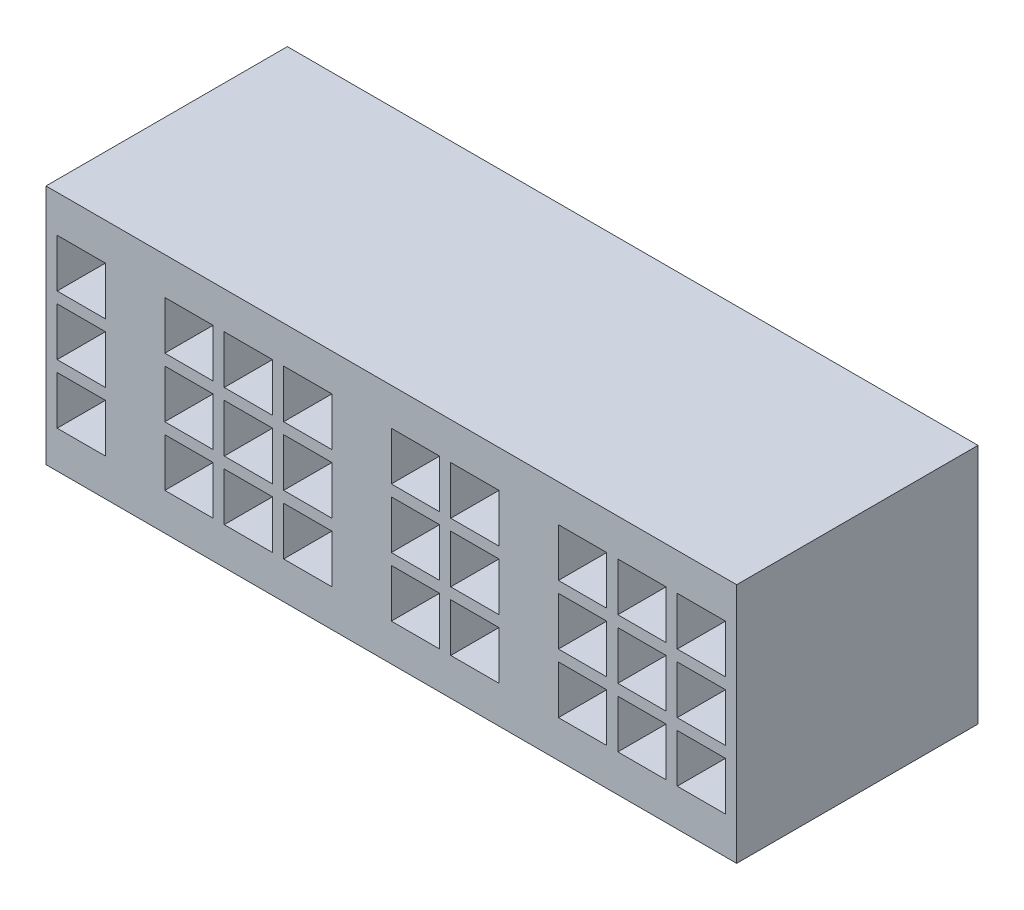
SolidWorks part; units mm, degrees
ref_plane "Plan de face" through (0, 0, 0) normal (0, 0, 1) x (1, 0, 0)
ref_plane "Plan de dessus" through (0, 0, 0) normal (0, 1, 0) x (1, 0, 0)
ref_plane "Plan de droite" through (0, 0, 0) normal (1, 0, 0) x (0, 0, -1)
sketch "Esquisse1" plane through (0, 0, 0) normal (0, 0, 1) x (1, 0, 0)
  line L1 (-93, -51) -> (93, -51)
  line L2 (-93, -51) -> (-93, 0)
  line L3 (-93, 0) -> (93, 0)
  line L4 (93, -51) -> (93, 0)
  line L13 (0, 49979.1071) -> (0, -49979.1071) construction
  point P0 (0, 0)
  point P16 (0, -51)
  point P17 (0, 0)
  point P27 (0, 0)
  dimension "D1" = 186
  dimension "D2" = 51
extrude "Boss.-Extru.1" add sketch "Esquisse1" along normal blind 35
sketch "Esquisse7" plane through (0, 0, 35) normal (0, 0, 1) x (1, 0, 0)
  line L0 (93, 0) -> (-93, 0) construction
  line L1 (-90, -3) -> (-77, -3)
  line L2 (-90, -3) -> (-90, -16)
  line L3 (-90, -16) -> (-77, -16)
  line L4 (-77, -3) -> (-77, -16)
  line L5 (-90, -3) -> (-77, -16) construction
  line L6 (-90, -16) -> (-77, -3) construction
  line L7 (-93, 0) -> (-93, -51) construction
  point P0 (-83.5, -9.5)
  dimension "D1" = 13
  dimension "D2" = 13
  dimension "D3" = 3
  dimension "D4" = 3
extrude "Enlèv. mat.-Extru.5" cut sketch "Esquisse7" against normal blind 91
pattern_linear "Répétition linéaire5" count 3 spacing 16 along (0, -1, 0) of "Enlèv. mat.-Extru.5"
sketch "Esquisse8" plane through (0, 0, 35) normal (0, 0, 1) x (1, 0, 0)
  line L0 (93, 0) -> (-93, 0) construction
  line L1 (-61, -3) -> (-48, -3)
  line L2 (-61, -3) -> (-61, -16)
  line L3 (-61, -16) -> (-48, -16)
  line L4 (-48, -3) -> (-48, -16)
  line L5 (-61, -3) -> (-48, -16) construction
  line L6 (-61, -16) -> (-48, -3) construction
  line L7 (-77, -16) -> (-77, -3) construction
  point P0 (-54.5, -9.5)
  dimension "D1" = 13
  dimension "D2" = 13
  dimension "D3" = 3
  dimension "D4" = 16
extrude "Enlèv. mat.-Extru.6" cut sketch "Esquisse8" against normal blind 103
pattern_linear "Répétition linéaire6" count 3 spacing 16 along (0, -1, 0) count 3 spacing 16 along (1, 0, 0) of "Enlèv. mat.-Extru.6"
sketch "Esquisse9" plane through (0, 0, 35) normal (0, 0, 1) x (1, 0, 0)
  line L0 (-16, -16) -> (-16, -3) construction
  line L1 (0, -3) -> (13, -3)
  line L2 (0, -3) -> (0, -16)
  line L3 (0, -16) -> (13, -16)
  line L4 (13, -3) -> (13, -16)
  line L5 (0, -3) -> (13, -16) construction
  line L6 (0, -16) -> (13, -3) construction
  line L7 (93, 0) -> (-93, 0) construction
  point P0 (6.5, -9.5)
  dimension "D1" = 13
  dimension "D2" = 13
  dimension "D3" = 16
  dimension "D4" = 3
extrude "Enlèv. mat.-Extru.7" cut sketch "Esquisse9" against normal blind 77
pattern_linear "Répétition linéaire7" count 3 spacing 16 along (0, -1, 0) count 2 spacing 16 along (1, 0, 0) of "Enlèv. mat.-Extru.7"
sketch "Esquisse10" plane through (0, 0, 35) normal (0, 0, 1) x (1, 0, 0)
  line L0 (29, -16) -> (29, -3) construction
  line L1 (45, -3) -> (58, -3)
  line L2 (45, -3) -> (45, -16)
  line L3 (45, -16) -> (58, -16)
  line L4 (58, -3) -> (58, -16)
  line L5 (45, -3) -> (58, -16) construction
  line L6 (45, -16) -> (58, -3) construction
  line L7 (93, 0) -> (-93, 0) construction
  point P0 (51.5, -9.5)
  dimension "D1" = 13
  dimension "D2" = 13
  dimension "D3" = 16
  dimension "D4" = 3
extrude "Enlèv. mat.-Extru.8" cut sketch "Esquisse10" against normal blind 78
pattern_linear "Répétition linéaire8" count 3 spacing 16 along (1, 0, 0) count 3 spacing 16 along (0, -1, 0) of "Enlèv. mat.-Extru.8"
sketch "Esquisse14" plane through (0, -51, 0) normal (0, -1, 0) x (1, 0, 0)
  line L0 (0, 0) -> (-15.3262, 0) construction
  line L1 (-12.6631, 0) -> (-2.6631, 0)
  line L2 (-12.6631, 0) -> (-12.6631, 5)
  line L3 (-12.6631, 5) -> (-2.6631, 5)
  line L4 (-2.6631, 0) -> (-2.6631, 5)
  line L5 (-12.6631, 0) -> (-2.6631, 5) construction
  line L6 (-12.6631, 5) -> (-2.6631, 0) construction
  line L7 (-93, 0) -> (93, 0) construction
  point P0 (-7.6631, 2.5)
  point P5 (-15.3262, 0)
  point P6 (0, 0)
  point P10 (0, 0)
  point P12 (-7.6631, 0)
  point P13 (-7.6631, 0)
  dimension "D1" = 10
  dimension "D2" = 5
extrude "Boss.-Extru.3" add sketch "Esquisse14" along normal blind 7
sketch "Esquisse25" plane through (0, 0, 0) normal (0, 1, 0) x (1, 0, 0)
  line L1 (-93, 0) -> (93, 0)
  line L2 (-93, 0) -> (-93, -35)
  line L3 (-93, -35) -> (93, -35)
  line L4 (93, 0) -> (93, -35)
extrude "Boss.-Extru.7" add sketch "Esquisse25" along normal blind 7
sketch "Esquisse18" plane through (0, -51, 0) normal (0, -1, 0) x (1, 0, 0)
  line L0 (-93, 0) -> (93, 0)
  line L2 (93, 0) -> (93, 35)
  line L3 (93, 35) -> (-93, 35)
  line L4 (-93, 35) -> (-93, 0)
extrude "Boss.-Extru.5" add sketch "Esquisse18" along normal blind 7
sketch "Esquisse16" plane through (-93, 0, 0) normal (-1, 0, 0) x (0, 0, 1)
  line L0 (35, -58) -> (0, -58) construction
  line L3 (33.3, -53) -> (30, -53)
  line L4 (30, -53) -> (30, 2)
  line L5 (30, 2) -> (33.3, 2)
  line L6 (33.3, 2) -> (33.3, -53)
  line L8 (0, 7) -> (35, 7) construction
  point P1 (31.65, -53)
  dimension "D1" = 5
  dimension "D4" = 5
  dimension "D5" = 3.3
sketch "Esquisse15" plane through (0, 0, 0) normal (0, 0, -1) x (-1, 0, 0)
  circle A0 centre (8.4823, -42.4466) radius 1
  circle A1 centre (8.4823, -9.749) radius 1
  circle A2 centre (68.823, -42.4466) radius 1
  circle A3 centre (68.823, -9.749) radius 1
  circle A4 centre (-37.1355, -42.4466) radius 1
  circle A5 centre (-39.2159, -11.2606) radius 1
  dimension "D1" = 2
  dimension "D2" = 2
  dimension "D3" = 2
  dimension "D4" = 2
  dimension "D5" = 2
  dimension "D6" = 2
extrude "Enlèv. mat.-Extru.10" cut sketch "Esquisse15" against normal blind 7
sketch "Esquisse24" plane through (0, 0, 0) normal (0, 0, -1) x (-1, 0, 0)
  line L0 (77, -48) -> (90, -48) construction
  line L1 (88.5, -48) -> (78.5, -48)
  line L2 (88.5, -48) -> (88.5, -50)
  line L3 (88.5, -50) -> (78.5, -50)
  line L4 (78.5, -48) -> (78.5, -50)
  line L5 (48, -48) -> (61, -48) construction
  line L6 (59.5, -48) -> (49.5, -48)
  line L7 (59.5, -48) -> (59.5, -50)
  line L8 (59.5, -50) -> (49.5, -50)
  line L9 (49.5, -48) -> (49.5, -50)
  line L10 (32, -48) -> (45, -48) construction
  line L11 (43.5, -48) -> (33.5, -48)
  line L12 (43.5, -48) -> (43.5, -50)
  line L13 (43.5, -50) -> (33.5, -50)
  line L14 (33.5, -48) -> (33.5, -50)
  line L15 (16, -48) -> (29, -48) construction
  line L16 (27.5, -48) -> (17.5, -48)
  line L17 (27.5, -48) -> (27.5, -50)
  line L18 (27.5, -50) -> (17.5, -50)
  line L19 (17.5, -48) -> (17.5, -50)
  line L20 (-13, -48) -> (0, -48) construction
  line L21 (-1.5, -48) -> (-11.5, -48)
  line L22 (-1.5, -48) -> (-1.5, -50)
  line L23 (-1.5, -50) -> (-11.5, -50)
  line L24 (-11.5, -48) -> (-11.5, -50)
  line L25 (-29, -48) -> (-16, -48) construction
  line L26 (-17.5, -48) -> (-27.5, -48)
  line L27 (-17.5, -48) -> (-17.5, -50)
  line L28 (-17.5, -50) -> (-27.5, -50)
  line L29 (-27.5, -48) -> (-27.5, -50)
  line L30 (-58, -48) -> (-45, -48) construction
  line L31 (-46.5, -48) -> (-56.5, -48)
  line L32 (-46.5, -48) -> (-46.5, -50)
  line L33 (-46.5, -50) -> (-56.5, -50)
  line L34 (-56.5, -48) -> (-56.5, -50)
  line L35 (-74, -48) -> (-61, -48) construction
  line L36 (-62.5, -48) -> (-72.5, -48)
  line L37 (-62.5, -48) -> (-62.5, -50)
  line L38 (-62.5, -50) -> (-72.5, -50)
  line L39 (-72.5, -48) -> (-72.5, -50)
  line L40 (-90, -48) -> (-77, -48) construction
  line L41 (-78.5, -48) -> (-88.5, -48)
  line L42 (-78.5, -48) -> (-78.5, -50)
  line L43 (-78.5, -50) -> (-88.5, -50)
  line L44 (-88.5, -48) -> (-88.5, -50)
  line L45 (-77, -3) -> (-90, -3) construction
  line L46 (-78.5, -3) -> (-88.5, -3)
  line L47 (-78.5, -3) -> (-78.5, -1)
  line L48 (-78.5, -1) -> (-88.5, -1)
  line L49 (-88.5, -3) -> (-88.5, -1)
  line L50 (-61, -3) -> (-74, -3) construction
  line L51 (-62.5, -3) -> (-72.5, -3)
  line L52 (-62.5, -3) -> (-62.5, -1)
  line L53 (-62.5, -1) -> (-72.5, -1)
  line L54 (-72.5, -3) -> (-72.5, -1)
  line L55 (-45, -3) -> (-58, -3) construction
  line L56 (-46.5, -3) -> (-56.5, -3)
  line L57 (-46.5, -3) -> (-46.5, -1)
  line L58 (-46.5, -1) -> (-56.5, -1)
  line L59 (-56.5, -3) -> (-56.5, -1)
  line L60 (-16, -3) -> (-29, -3) construction
  line L61 (-17.5, -3) -> (-27.5, -3)
  line L62 (-17.5, -3) -> (-17.5, -1)
  line L63 (-17.5, -1) -> (-27.5, -1)
  line L64 (-27.5, -3) -> (-27.5, -1)
  line L65 (0, -3) -> (-13, -3) construction
  line L66 (-1.5, -3) -> (-11.5, -3)
  line L67 (-1.5, -3) -> (-1.5, -1)
  line L68 (-1.5, -1) -> (-11.5, -1)
  line L69 (-11.5, -3) -> (-11.5, -1)
  line L70 (29, -3) -> (16, -3) construction
  line L71 (17.5, -3) -> (27.5, -3)
  line L72 (17.5, -3) -> (17.5, -1)
  line L73 (17.5, -1) -> (27.5, -1)
  line L74 (27.5, -3) -> (27.5, -1)
  line L75 (45, -3) -> (32, -3) construction
  line L76 (33.5, -3) -> (43.5, -3)
  line L77 (33.5, -3) -> (33.5, -1)
  line L78 (33.5, -1) -> (43.5, -1)
  line L79 (43.5, -3) -> (43.5, -1)
  line L80 (61, -3) -> (48, -3) construction
  line L81 (49.5, -3) -> (59.5, -3)
  line L82 (49.5, -3) -> (49.5, -1)
  line L83 (49.5, -1) -> (59.5, -1)
  line L84 (59.5, -3) -> (59.5, -1)
  line L85 (90, -3) -> (77, -3) construction
  line L86 (78.5, -3) -> (88.5, -3)
  line L87 (78.5, -3) -> (78.5, -1)
  line L88 (78.5, -1) -> (88.5, -1)
  line L89 (88.5, -3) -> (88.5, -1)
  point P108 (83.5, -48)
  point P109 (54.5, -48)
  point P110 (38.5, -48)
  point P111 (22.5, -48)
  point P112 (-6.5, -48)
  point P113 (-22.5, -48)
  point P114 (-51.5, -48)
  point P115 (-67.5, -48)
  point P116 (-83.5, -48)
  point P117 (-83.5, -3)
  point P118 (-67.5, -3)
  point P119 (-51.5, -3)
  point P120 (-22.5, -3)
  point P121 (-6.5, -3)
  point P122 (22.5, -3)
  point P123 (38.5, -3)
  point P124 (54.5, -3)
  point P125 (83.5, -3)
  point P126 (83.5, -3)
  point P128 (54.5, -3)
  point P130 (38.5, -3)
  point P132 (22.5, -3)
  point P134 (-6.5, -3)
  point P136 (-22.5, -3)
  point P138 (-51.5, -3)
  point P140 (-67.5, -3)
  point P143 (-83.5, -3)
  point P145 (-83.5, -48)
  point P148 (-51.5, -48)
  point P150 (-22.5, -48)
  point P152 (-6.5, -48)
  point P154 (22.5, -48)
  point P156 (38.5, -48)
  point P159 (54.5, -48)
  point P161 (83.5, -48)
  dimension "D1" = 10
  dimension "D2" = 10
  dimension "D3" = 10
  dimension "D4" = 10
  dimension "D5" = 10
  dimension "D6" = 10
  dimension "D7" = 10
  dimension "D8" = 10
  dimension "D9" = 10
  dimension "D10" = 10
  dimension "D11" = 10
  dimension "D12" = 10
  dimension "D13" = 10
  dimension "D14" = 10
  dimension "D15" = 10
  dimension "D16" = 10
  dimension "D17" = 10
  dimension "D18" = 10
  dimension "D19" = 2
  dimension "D20" = 2
  dimension "D21" = 2
  dimension "D22" = 2
  dimension "D23" = 2
  dimension "D24" = 2
  dimension "D25" = 2
  dimension "D26" = 2
  dimension "D27" = 2
  dimension "D28" = 2
  dimension "D29" = 2
  dimension "D30" = 2
  dimension "D31" = 2
  dimension "D32" = 2
  dimension "D33" = 2
  dimension "D34" = 2
  dimension "D35" = 2
  dimension "D36" = 2
extrude "Enlèv. mat.-Extru.12" cut sketch "Esquisse24" against normal blind 1
sketch "Esquisse19" plane through (0, 0, 0) normal (0, 0, -1) x (-1, 0, 0)
  line L0 (-93, -58) -> (-93, 7) construction
  line L1 (93, -58) -> (-93, -58)
  line L2 (93, -58) -> (93, -57)
  line L3 (93, -57) -> (-93, -57)
  line L4 (-93, -58) -> (-93, -57)
  line L5 (93, 7) -> (93, -58) construction
  line L6 (-93, 7) -> (93, 7)
  line L7 (-93, 7) -> (-93, 6)
  line L8 (-93, 6) -> (93, 6)
  line L9 (93, 7) -> (93, 6)
  line L11 (-93, -57) -> (-92, -57)
  line L12 (-93, -57) -> (-93, 6)
  line L13 (-93, 6) -> (-92, 6)
  line L14 (-92, -57) -> (-92, 6)
  line L15 (93, 6) -> (92, 6)
  line L16 (93, 6) -> (93, -57)
  line L17 (93, -57) -> (92, -57)
  line L18 (92, 6) -> (92, -57)
  dimension "D1" = 1
  dimension "D2" = 1
  dimension "D3" = 1
  dimension "D4" = 1
extrude "Boss.-Extru.8" add sketch "Esquisse19" along normal blind 30 contours L4 L1 L2 L3 | L8 L18 L3 L16 | L9 L6 L7 L8 | L3 L14 L8 L12
sketch "Esquisse26" plane through (-93, 0, 0) normal (-1, 0, 0) x (0, 0, 1)
  line L0 (-30, -58) -> (2.5, 7) construction
  line L1 (-30, 7) -> (35, 7) construction
  line L2 (-30, 7) -> (2.5, -58) construction
  line L3 (35, -58) -> (-30, -58) construction
  circle A0 centre (-13.75, -25.5) radius 1.75
  dimension "D1" = 3.5
extrude "Enlèv. mat.-Extru.14" cut sketch "Esquisse26" against normal blind 30
